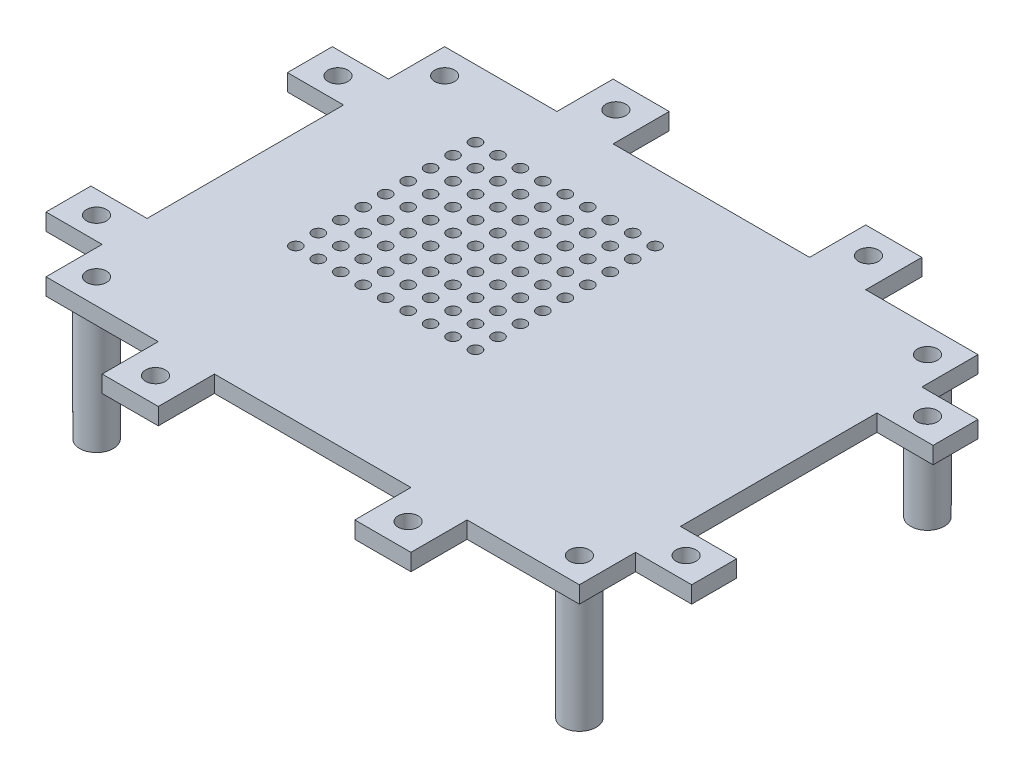
SolidWorks part; units mm, degrees
ref_plane "Front Plane" through (0, 0, 0) normal (0, 0, 1) x (1, 0, 0)
ref_plane "Top Plane" through (0, 0, 0) normal (0, 1, 0) x (1, 0, 0)
ref_plane "Right Plane" through (0, 0, 0) normal (1, 0, 0) x (0, 0, -1)
sketch "Sketch1" plane through (0, 0, 0) normal (0, 1, 0) x (1, 0, 0)
  line L0 (-50.9322, 25.9523) -> (-50.9322, 35.9523)
  line L1 (-50.9322, -35.0477) -> (-30.9322, -35.0477)
  line L2 (-50.9322, -35.0477) -> (-50.9322, -25.0477)
  line L3 (-50.9322, 35.9523) -> (-30.9322, 35.9523)
  line L4 (44.0678, -35.0477) -> (44.0678, -25.0477)
  line L5 (-50.9322, 17.9523) -> (-60.9322, 17.9523)
  line L6 (-50.9322, -17.0477) -> (-50.9322, 17.9523)
  line L7 (-50.9322, 25.9523) -> (-60.9322, 25.9523)
  line L8 (-60.9322, 17.9523) -> (-60.9322, 25.9523)
  line L9 (-50.9322, -25.0477) -> (-60.9322, -25.0477)
  line L10 (44.0678, 25.9523) -> (44.0678, 35.9523)
  line L11 (-50.9322, -17.0477) -> (-60.9322, -17.0477)
  line L12 (-60.9322, -25.0477) -> (-60.9322, -17.0477)
  line L13 (44.0678, 25.9523) -> (54.0678, 25.9523)
  line L14 (44.0678, -17.0477) -> (44.0678, 17.9523)
  line L15 (44.0678, 17.9523) -> (54.0678, 17.9523)
  line L16 (54.0678, 25.9523) -> (54.0678, 17.9523)
  line L17 (44.0678, -25.0477) -> (54.0678, -25.0477)
  line L18 (-20.9322, 35.9523) -> (14.0678, 35.9523)
  line L19 (44.0678, -17.0477) -> (54.0678, -17.0477)
  line L20 (54.0678, -25.0477) -> (54.0678, -17.0477)
  line L21 (24.0678, 35.9523) -> (44.0678, 35.9523)
  line L22 (-30.9322, 35.9523) -> (-30.9322, 45.9523)
  line L23 (-30.9322, 45.9523) -> (-20.9322, 45.9523)
  line L24 (-20.9322, 35.9523) -> (-20.9322, 45.9523)
  line L25 (-20.9322, -35.0477) -> (14.0678, -35.0477)
  line L26 (14.0678, 35.9523) -> (14.0678, 45.9523)
  line L27 (14.0678, 45.9523) -> (24.0678, 45.9523)
  line L28 (24.0678, 35.9523) -> (24.0678, 45.9523)
  line L29 (24.0678, -35.0477) -> (44.0678, -35.0477)
  line L30 (-30.9322, -35.0477) -> (-30.9322, -45.0477)
  line L31 (-30.9322, -45.0477) -> (-20.9322, -45.0477)
  line L32 (-20.9322, -35.0477) -> (-20.9322, -45.0477)
  line L34 (14.0678, -35.0477) -> (14.0678, -45.0477)
  line L35 (14.0678, -45.0477) -> (24.0678, -45.0477)
  line L36 (24.0678, -35.0477) -> (24.0678, -45.0477)
  dimension "D1" = 95
  dimension "D2" = 71
  dimension "D3" = 10
  dimension "D4" = 8
  dimension "D5" = 35
  dimension "D6" = 35
  dimension "D7" = 10
  dimension "D8" = 10
extrude "Boss-Extrude1" add sketch "Sketch1" along normal blind 3
sketch "Sketch2" plane through (0, 0, 0) normal (0, -1, 0) x (1, 0, 0)
  line L0 (-46.4322, 30.5477) -> (-46.4322, -31.4523) construction
  line L1 (-46.4322, -31.4523) -> (39.5678, -31.4523) construction
  line L2 (39.5678, -31.4523) -> (39.5678, 30.5477) construction
  line L3 (39.5678, 30.5477) -> (-46.4322, 30.5477) construction
  line L4 (-50.9322, 25.0477) -> (-50.9322, 35.0477) construction
  line L5 (-30.9322, -35.9523) -> (-50.9322, -35.9523) construction
  line L6 (44.0678, 35.0477) -> (44.0678, 25.0477) construction
  line L7 (-50.9322, 35.0477) -> (-30.9322, 35.0477) construction
  circle A0 centre (-46.4322, 30.5477) radius 3
  circle A1 centre (-46.4322, -31.4523) radius 3
  circle A2 centre (39.5678, -31.4523) radius 3
  circle A3 centre (39.5678, 30.5477) radius 3
  dimension "D5" = 6
  dimension "D1" = 4.5
  dimension "D2" = 4.5
  dimension "D3" = 4.5
  dimension "D4" = 4.5
extrude "Boss-Extrude2" add sketch "Sketch2" along normal blind 22
sketch "Sketch3" plane through (0, -22, 0) normal (0, -1, 0) x (1, 0, 0)
  circle A0 centre (-46.4322, 30.5477) radius 1.775
  circle A1 centre (-46.4322, -31.4523) radius 1.775
  circle A2 centre (39.5678, -31.4523) radius 1.775
  circle A3 centre (39.5678, 30.5477) radius 1.775
  circle A4 centre (-46.4322, 30.5477) radius 3 construction
  circle A5 centre (-46.4322, -31.4523) radius 3 construction
  circle A6 centre (39.5678, -31.4523) radius 3 construction
  circle A7 centre (39.5678, 30.5477) radius 3 construction
  dimension "D1" = 3.55
extrude "Cut-Extrude1" cut sketch "Sketch3" against normal through all
sketch "Sketch4" plane through (0, 3, 0) normal (0, 1, 0) x (1, 0, 0)
  line L0 (-50.9322, -25.0477) -> (-50.9322, -35.0477) construction
  line L1 (-30.9322, 35.9523) -> (-50.9322, 35.9523) construction
  circle A0 centre (-33.4322, 23.9523) radius 1.05
  dimension "D3" = 2.1
  dimension "D1" = 17.5
  dimension "D2" = 12
extrude "Cut-Extrude2" cut sketch "Sketch4" against normal through all
pattern_linear "LPattern1" count 9 spacing 4 along (1, 0, 0) count 9 spacing 4 along (0, 0, 1) of "Cut-Extrude2"
sketch "Sketch5" plane through (0, 3, 0) normal (0, 1, 0) x (1, 0, 0)
  line L0 (-55.9322, 17.9523) -> (-55.9322, 21.9523) construction
  line L1 (-55.9322, 21.9523) -> (49.0678, 21.9523) construction
  line L2 (-60.9322, 17.9523) -> (-50.9322, 17.9523) construction
  line L3 (49.0678, -21.0477) -> (-55.9322, -21.0477) construction
  line L4 (-55.9322, 21.9523) -> (-55.9322, 25.9523) construction
  line L5 (-50.9322, 25.9523) -> (-60.9322, 25.9523) construction
  line L6 (-55.9322, -25.0477) -> (-55.9322, -21.0477) construction
  line L7 (-60.9322, -25.0477) -> (-50.9322, -25.0477) construction
  line L8 (-55.9322, -21.0477) -> (-55.9322, -17.0477) construction
  line L9 (-50.9322, -17.0477) -> (-60.9322, -17.0477) construction
  line L10 (49.0678, -25.0477) -> (49.0678, -21.0477) construction
  line L11 (44.0678, -25.0477) -> (54.0678, -25.0477) construction
  line L12 (49.0678, -21.0477) -> (49.0678, -17.0477) construction
  line L13 (54.0678, -17.0477) -> (44.0678, -17.0477) construction
  line L14 (49.0678, 17.9523) -> (49.0678, 21.9523) construction
  line L15 (44.0678, 17.9523) -> (54.0678, 17.9523) construction
  line L16 (49.0678, 21.9523) -> (49.0678, 25.9523) construction
  line L17 (54.0678, 25.9523) -> (44.0678, 25.9523) construction
  line L18 (-55.9322, -17.0477) -> (-50.9322, -17.0477) construction
  line L19 (44.0678, -17.0477) -> (49.0678, -17.0477) construction
  circle A0 centre (-55.9322, -21.0477) radius 1.775
  circle A1 centre (-55.9322, 21.9523) radius 1.775
  circle A2 centre (49.0678, 21.9523) radius 1.775
  circle A3 centre (49.0678, -21.0477) radius 1.775
  dimension "D1" = 3.55
  dimension "D2" = 105
  dimension "D3" = 43
extrude "Cut-Extrude3" cut sketch "Sketch5" against normal through all
sketch "Sketch6" plane through (0, 3, 0) normal (0, 1, 0) x (1, 0, 0)
  line L0 (-25.9322, -40.5477) -> (-25.9322, 41.4523) construction
  line L1 (-25.9322, 41.4523) -> (19.0678, 41.4523) construction
  line L2 (19.0678, 41.4523) -> (19.0678, -40.5477) construction
  line L3 (19.0678, -40.5477) -> (-25.9322, -40.5477) construction
  line L4 (-4.8072, -40.5477) -> (-4.8072, -35.0477) construction
  line L5 (-20.9322, -35.0477) -> (14.0678, -35.0477) construction
  line L6 (-3.4322, 35.9523) -> (-3.4322, 41.4523) construction
  line L7 (14.0678, 35.9523) -> (-20.9322, 35.9523) construction
  line L8 (-30.9322, 35.9523) -> (-25.9322, 35.9523) construction
  line L9 (-25.9322, 35.9523) -> (-20.9322, 35.9523) construction
  line L10 (14.0678, 35.9523) -> (19.0678, 35.9523) construction
  line L11 (19.0678, 35.9523) -> (24.0678, 35.9523) construction
  line L12 (-30.9322, -35.0477) -> (-25.9322, -35.0477) construction
  line L13 (-25.9322, -35.0477) -> (-20.9322, -35.0477) construction
  line L14 (14.0678, -35.0477) -> (19.0678, -35.0477) construction
  line L15 (19.0678, -35.0477) -> (24.0678, -35.0477) construction
  circle A0 centre (-25.9322, 41.4523) radius 1.775
  circle A1 centre (19.0678, 41.4523) radius 1.775
  circle A2 centre (-25.9322, -40.5477) radius 1.775
  circle A3 centre (19.0678, -40.5477) radius 1.775
  dimension "D1" = 3.55
  dimension "D2" = 82
  dimension "D3" = 45
extrude "Cut-Extrude4" cut sketch "Sketch6" against normal through all
